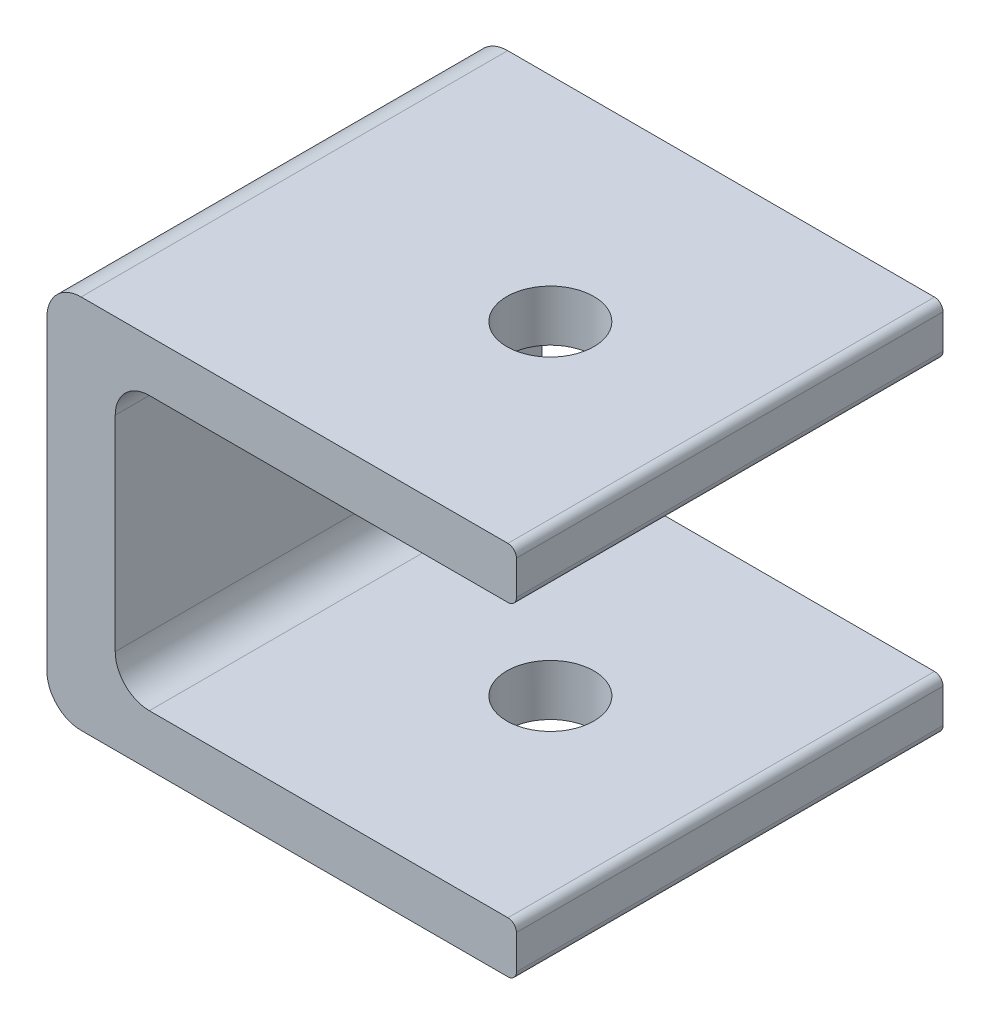
SolidWorks part; units mm, degrees
ref_plane "前视基准面" through (0, 0, 0) normal (0, 0, 1) x (1, 0, 0)
ref_plane "上视基准面" through (0, 0, 0) normal (0, 1, 0) x (1, 0, 0)
ref_plane "右视基准面" through (0, 0, 0) normal (1, 0, 0) x (0, 0, -1)
sketch "草图1" plane through (0, 0, 0) normal (0, 0, 1) x (1, 0, 0)
  line L1 (0, 0) -> (23.5126, 0)
  line L3 (0, 3) -> (23.5126, 3)
  line L4 (23.5126, 0) -> (23.5126, 3)
  line L5 (0, 3) -> (-4, 3)
  line L6 (0, 0) -> (0, -16)
  line L7 (0, -19) -> (-4, -19)
  line L8 (-4, 3) -> (-4, -19)
  line L9 (0, -19) -> (23.5126, -19)
  line L11 (0, -16) -> (23.5126, -16)
  line L12 (23.5126, -19) -> (23.5126, -16)
  dimension "D1" = 22
  dimension "D2" = 4
  dimension "D3" = 3
  dimension "D4" = 3
extrude "凸台-拉伸1" add sketch "草图1" along normal blind 25
sketch "草图2" plane through (-4, 0, 0) normal (-1, 0, 0) x (0, 0, 1)
  line L1 (25, -19) -> (0, -19) construction
  circle A1 centre (12.5, -8) radius 2.55
  dimension "D1" = 5.1
  dimension "D2" = 11
extrude "切除-拉伸1" cut sketch "草图2" against normal blind 5
fillet "圆角1" radius 2 4 edges at (0, 0, 12.5) (0, -16, 12.5) (-4, -19, 12.5) (-4, 3, 12.5)
fillet "圆角2" radius 0.5 4 edges at (23.5126, -19, 12.5) (23.5126, -16, 12.5) (23.5126, 0, 12.5) (23.5126, 3, 12.5)
sketch "草图3" plane through (0, 3, 0) normal (0, 1, 0) x (1, 0, 0)
  circle A0 centre (13, -12.5) radius 2.55
extrude "切除-拉伸2" cut sketch "草图3" against normal blind 35
